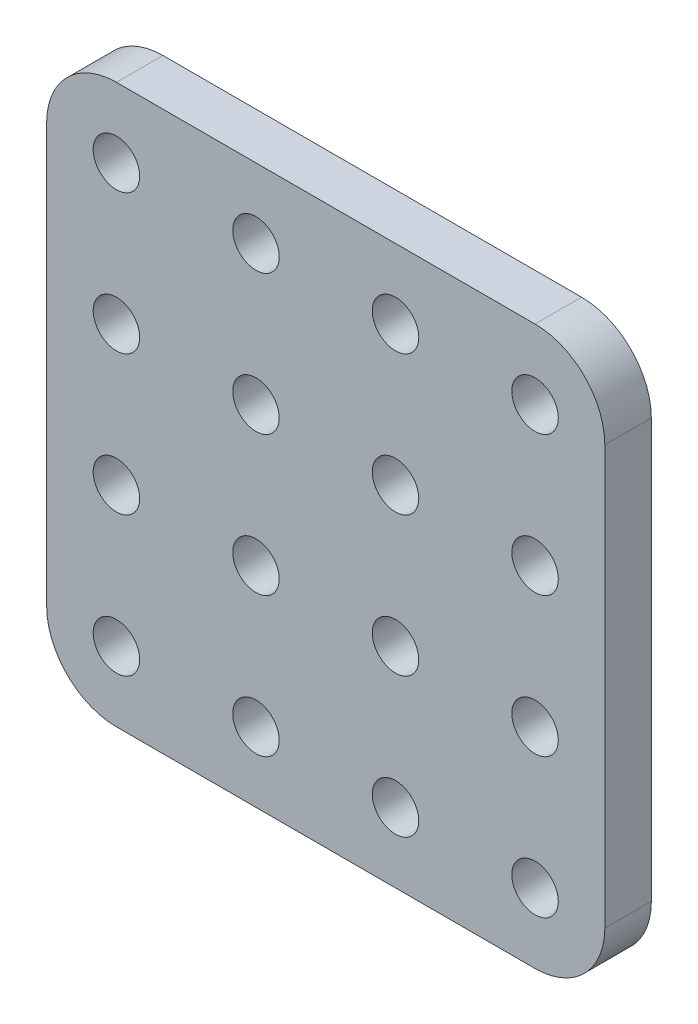
SolidWorks part; units mm, degrees
ref_plane "Alzado" through (0, 0, 0) normal (0, 0, 1) x (1, 0, 0)
ref_plane "Planta" through (0, 0, 0) normal (0, 1, 0) x (1, 0, 0)
ref_plane "Vista lateral" through (0, 0, 0) normal (1, 0, 0) x (0, 0, -1)
sketch "Model" plane through (0, 0, 0) normal (0, 0, 1) x (1, 0, 0)
  line L0 (-105.9434, 101.0565) -> (-105.9434, 74.0565)
  line L1 (-101.4434, 69.5565) -> (-74.4434, 69.5565)
  line L2 (-69.9434, 74.0565) -> (-69.9434, 101.0565)
  line L3 (-74.4434, 105.5565) -> (-101.4434, 105.5565)
  circle A0 centre (-101.4434, 101.0565) radius 1.5
  circle A1 centre (-92.4434, 101.0565) radius 1.5
  circle A2 centre (-83.4434, 101.0565) radius 1.5
  circle A3 centre (-74.4434, 101.0565) radius 1.5
  circle A4 centre (-101.4434, 92.0565) radius 1.5
  circle A5 centre (-92.4434, 92.0565) radius 1.5
  circle A6 centre (-83.4434, 92.0565) radius 1.5
  circle A7 centre (-74.4434, 92.0565) radius 1.5
  circle A8 centre (-101.4434, 83.0565) radius 1.5
  circle A9 centre (-92.4434, 83.0565) radius 1.5
  circle A10 centre (-83.4434, 83.0565) radius 1.5
  circle A11 centre (-74.4434, 83.0565) radius 1.5
  circle A12 centre (-101.4434, 74.0565) radius 1.5
  circle A13 centre (-92.4434, 74.0565) radius 1.5
  circle A14 centre (-83.4434, 74.0565) radius 1.5
  circle A15 centre (-74.4434, 74.0565) radius 1.5
  arc A16 (-101.4434, 105.5565) -> (-105.9434, 101.0565) centre (-101.4434, 101.0565) ccw
  arc A17 (-69.9434, 101.0565) -> (-74.4434, 105.5565) centre (-74.4434, 101.0565) ccw
  arc A18 (-105.9434, 74.0565) -> (-101.4434, 69.5565) centre (-101.4434, 74.0565) ccw
  arc A19 (-74.4434, 69.5565) -> (-69.9434, 74.0565) centre (-74.4434, 74.0565) ccw
extrude "Saliente-Extruir1" add sketch "Model" along normal blind 3
